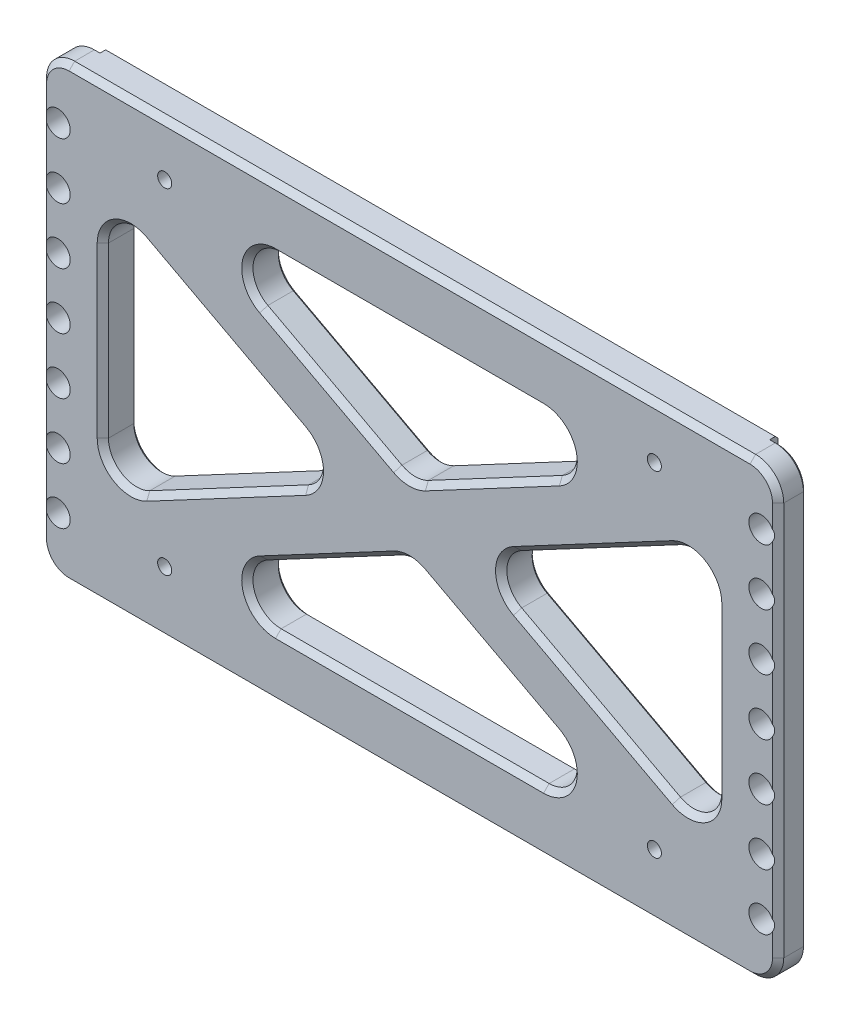
SolidWorks part; units mm, degrees
material "7075-T6 (SN)"
ref_plane "前视基准面" through (0, 0, 0) normal (0, 0, 1) x (1, 0, 0)
ref_plane "上视基准面" through (0, 0, 0) normal (0, 1, 0) x (1, 0, 0)
ref_plane "右视基准面" through (0, 0, 0) normal (1, 0, 0) x (0, 0, -1)
sketch "草图3" plane through (0, 0, 0) normal (0, 0, 1) x (1, 0, 0)
  line L0 (-57.5, -11.5) -> (57.5, -11.5) construction
  line L1 (-65.5, -11.5) -> (65.5, -11.5)
  line L2 (-65.5, -91.5) -> (65.5, -91.5)
  line L3 (65.5, -5.5) -> (65.5, -101.8916) construction
  line L4 (-65.5, -101.8916) -> (-65.5, -5.5) construction
  line L5 (65.5, -11.5) -> (65.5, -91.5)
  line L6 (-65.5, -91.5) -> (-65.5, -11.5)
  line L7 (-57.5, -11.5) -> (57.5, -11.5) construction
  line L8 (-57.5, -91.5) -> (57.5, -91.5) construction
  dimension "D1" = 80
extrude "凸台-拉伸3" add sketch "草图3" along normal blind 5
sketch "草图4" plane through (0, 0, 5) normal (0, 0, 1) x (1, 0, 0)
  line L0 (-65.5, -91.5) -> (65.5, -91.5) construction
  line L1 (59.5, -91.5) -> (-59.5, -91.5)
  line L2 (59.5, -91.5) -> (59.5, -11.5)
  line L3 (59.5, -11.5) -> (-59.5, -11.5)
  line L4 (-59.5, -91.5) -> (-59.5, -11.5)
  line L5 (59.5, -11.5) -> (59.5, -101.8916) construction
  line L6 (60.5, -11.5) -> (-60.5, -11.5) construction
  line L7 (65.5, -11.5) -> (-65.5, -11.5) construction
extrude "凸台-拉伸4" add sketch "草图4" against normal blind 6
fillet "圆角2" radius 5 4 edges at (65.5, -11.5, 2.5) (-65.5, -11.5, 2.5) (-65.5, -91.5, 2.5) (65.5, -91.5, 2.5)
chamfer "倒角1" distance 1 angle 45 8 edges at (-65.5, -51.5, 5) (-64.0355, -90.0355, 5) (-64.0355, -12.9645, 5) (0, -91.5, 5) (0, -11.5, 5) (64.0355, -90.0355, 5) (64.0355, -12.9645, 5) (65.5, -51.5, 5)
sketch "草图5" plane through (0, 0, 5) normal (0, 0, 1) x (1, 0, 0)
  line L4 (-54.5, -22.5) -> (54.5, -80.5)
  line L5 (-54.5, -80.5) -> (54.5, -22.5)
  line L6 (-52.1513, -84.914) -> (56.8487, -26.914)
  line L7 (-56.8487, -26.914) -> (52.1513, -84.914)
  line L8 (-54.5, -22.5) -> (-54.5, -80.5)
  line L9 (-54.5, -80.5) -> (54.5, -80.5)
  line L10 (54.5, -80.5) -> (54.5, -22.5)
  line L11 (54.5, -22.5) -> (-54.5, -22.5)
  line L12 (-54.5, -22.5) -> (-54.5, -80.5)
  line L13 (-54.5, -80.5) -> (54.5, -80.5)
  line L14 (54.5, -80.5) -> (54.5, -22.5)
  line L15 (54.5, -22.5) -> (-54.5, -22.5)
  line L16 (-56.8487, -76.086) -> (52.1513, -18.086)
  line L17 (-52.1513, -18.086) -> (56.8487, -76.086)
  dimension "D2" = 5
  dimension "D1" = 10
  dimension "D3" = 5
extrude "切除-拉伸1" cut sketch "草图5" against normal blind 6 contours L12 L16 L7 | L15 L17 L16 | L6 L17 L14 | L6 L13 L7
fillet "圆角3" radius 5 12 edges at (54.5, -28.1638, 2) (54.5, -74.8362, 2) (10.644, -51.5, 2) (0, -45.8362, 2) (-43.856, -22.5, 2) (43.856, -22.5, 2) (-10.644, -51.5, 2) (-54.5, -74.8362, 2) (-54.5, -28.1638, 2) (0, -57.1638, 2) (43.856, -80.5, 2) (-43.856, -80.5, 2)
chamfer "倒角2" distance 1 angle 45 24 edges at (-52.0745, -70.7981, 5) (-54.5, -51.5, 5) (-33.0453, -63.4199, 5) (-52.0745, -32.2019, 5) (-16.288, -51.5, 5) (-33.0453, -39.5801, 5) (28.6667, -26.2896, 5) (0, -22.5, 5) (14.2564, -38.2502, 5) (-28.6667, -26.2896, 5) (0, -45.1724, 5) (-14.2564, -38.2502, 5) (52.0745, -32.2019, 5) (33.0453, -39.5801, 5) (54.5, -51.5, 5) (16.288, -51.5, 5) (52.0745, -70.7981, 5) (33.0453, -63.4199, 5) (-28.6667, -76.7104, 5) (-14.2564, -64.7498, 5) (0, -80.5, 5) (0, -57.8276, 5) (28.6667, -76.7104, 5) (14.2564, -64.7498, 5)
sketch "草图6" plane through (0, 0, 5) normal (0, 0, 1) x (1, 0, 0)
  line L0 (65.5, -51.5) -> (59.5, -51.5) construction
  line L1 (65.5, -16.5) -> (65.5, -86.5) construction
  line L2 (62.5, -41.5) -> (62.5, -61.5) construction
  line L3 (62.5, -31.5) -> (62.5, -71.5) construction
  line L4 (62.5, -21.5) -> (62.5, -81.5) construction
  circle A0 centre (62.5, -21.5) radius 2.2
  circle A1 centre (62.5, -31.5) radius 2.2
  circle A2 centre (62.5, -41.5) radius 2.2
  circle A3 centre (62.5, -51.5) radius 2.2
  circle A4 centre (62.5, -61.5) radius 2.2
  circle A5 centre (62.5, -71.5) radius 2.2
  circle A6 centre (62.5, -81.5) radius 2.2
  point P7 (62.5, -51.5)
  point P11 (62.5, -51.5)
  point P14 (62.5, -51.5)
  dimension "D1" = 7
extrude "切除-拉伸2" cut sketch "草图6" against normal blind 11
mirror "镜向1" about plane through (0, 0, 0) normal (1, 0, 0) of "切除-拉伸2"
sketch "草图7" plane through (0, 0, 5) normal (0, 0, 1) x (1, 0, 0)
  line L0 (0, -90.5) -> (0, -50.52) construction
  line L1 (-60.5, -90.5) -> (60.5, -90.5) construction
  line L3 (-43.51, -80.29) -> (43.51, -80.29)
  line L4 (-43.51, -80.29) -> (-43.51, -20.75)
  line L5 (-43.51, -20.75) -> (43.51, -20.75)
  line L6 (43.51, -80.29) -> (43.51, -20.75)
  line L7 (-43.51, -80.29) -> (43.51, -20.75) construction
  line L8 (-43.51, -20.75) -> (43.51, -80.29) construction
hole_wizard "M3 螺纹孔1" positions "草图8" profile "草图9" tap size "M3" standard "GB"
sketch "草图8" plane through (0, 0, 5) normal (0, 0, 1) x (1, 0, 0)
  point P0 (-43.51, -20.75)
  point P3 (43.51, -20.75)
  point P6 (43.51, -80.29)
  point P9 (-43.51, -80.29)
sketch "草图9" plane through (-43.51, -20.75, 5) normal (1, 0, 0) x (0, -1, 0)
  line L0 (0, 0) -> (0, 8.2511)
  line L1 (0, 8.2511) -> (1.25, 7.5)
  line L2 (1.25, 7.5) -> (1.25, 0)
  line L5 (1.25, 0) -> (0, 0)
  line L10 (0, 8.2511) -> (-1.25, 7.5) construction
  line L11 (0, -6.35) -> (0, 107.95) construction
  dimension "螺纹孔钻头直径" = 2.5
  dimension "螺纹孔钻头深度" = 7.5
  dimension "导头角度" = 118
cosmetic thread "孔螺蚊线1" parameters "D1"=6, "D2"=3
cosmetic thread "孔螺蚊线2" parameters "D1"=6, "D2"=3
cosmetic thread "孔螺蚊线3" parameters "D1"=6, "D2"=3
cosmetic thread "孔螺蚊线4" parameters "D1"=6, "D2"=3
chamfer "倒角3" distance 0.5 angle 45 36 edges at (-60, -11.5, 0) (-64.0355, -12.9645, 0) (-60, -91.5, 0) (-65.5, -51.5, 0) (-64.0355, -90.0355, 0) (0, -91.5, -1) (60, -91.5, 0) (64.0355, -90.0355, 0) (60, -11.5, 0) (65.5, -51.5, 0) (64.0355, -12.9645, 0) (0, -11.5, -1) (52.0745, -70.7981, -1) (33.0453, -63.4199, -1) (54.5, -51.5, -1) (16.288, -51.5, -1) (52.0745, -32.2019, -1) (33.0453, -39.5801, -1) (0, -80.5, -1) (28.6667, -76.7104, -1) (-28.6667, -76.7104, -1) (14.2564, -64.7498, -1) (-14.2564, -64.7498, -1) (0, -57.8276, -1) (-52.0745, -70.7981, -1) (-54.5, -51.5, -1) (-33.0453, -63.4199, -1) (-52.0745, -32.2019, -1) (-16.288, -51.5, -1) (-33.0453, -39.5801, -1) (0, -45.1724, -1) (14.2564, -38.2502, -1) (-14.2564, -38.2502, -1) (28.6667, -26.2896, -1) (-28.6667, -26.2896, -1) (0, -22.5, -1)
